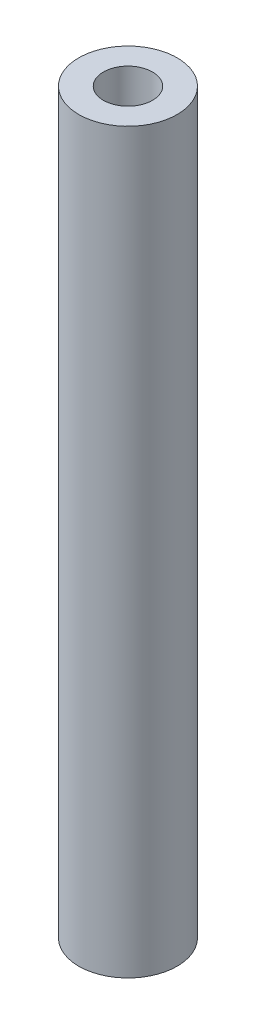
SolidWorks part; units mm, degrees
ref_plane "前视基准面" through (0, 0, 0) normal (0, 0, 1) x (1, 0, 0)
ref_plane "上视基准面" through (0, 0, 0) normal (0, 1, 0) x (1, 0, 0)
ref_plane "右视基准面" through (0, 0, 0) normal (1, 0, 0) x (0, 0, -1)
sketch "草图1" plane through (0, 0, 0) normal (0, 1, 0) x (1, 0, 0)
  circle A0 centre (0, 0) radius 2
  circle A1 centre (0, 0) radius 1
extrude "凸台-拉伸1" add sketch "草图1" along normal blind 30
